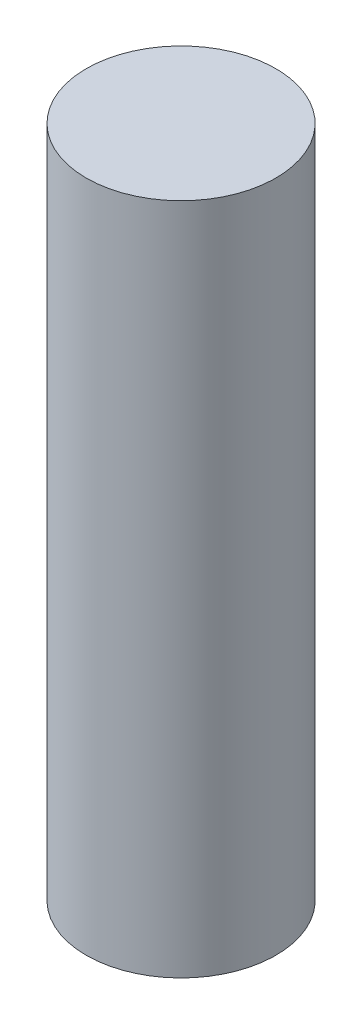
SolidWorks part; units mm, degrees
ref_plane "Front Plane" through (0, 0, 0) normal (0, 0, 1) x (1, 0, 0)
ref_plane "Top Plane" through (0, 0, 0) normal (0, 1, 0) x (1, 0, 0)
ref_plane "Right Plane" through (0, 0, 0) normal (1, 0, 0) x (0, 0, -1)
sketch "Sketch1" plane through (0, 0, 0) normal (0, 1, 0) x (1, 0, 0)
  circle A0 centre (0, 0) radius 1
  dimension "D1" = 2
extrude "Boss-Extrude1" add sketch "Sketch1" along normal blind 7.1
